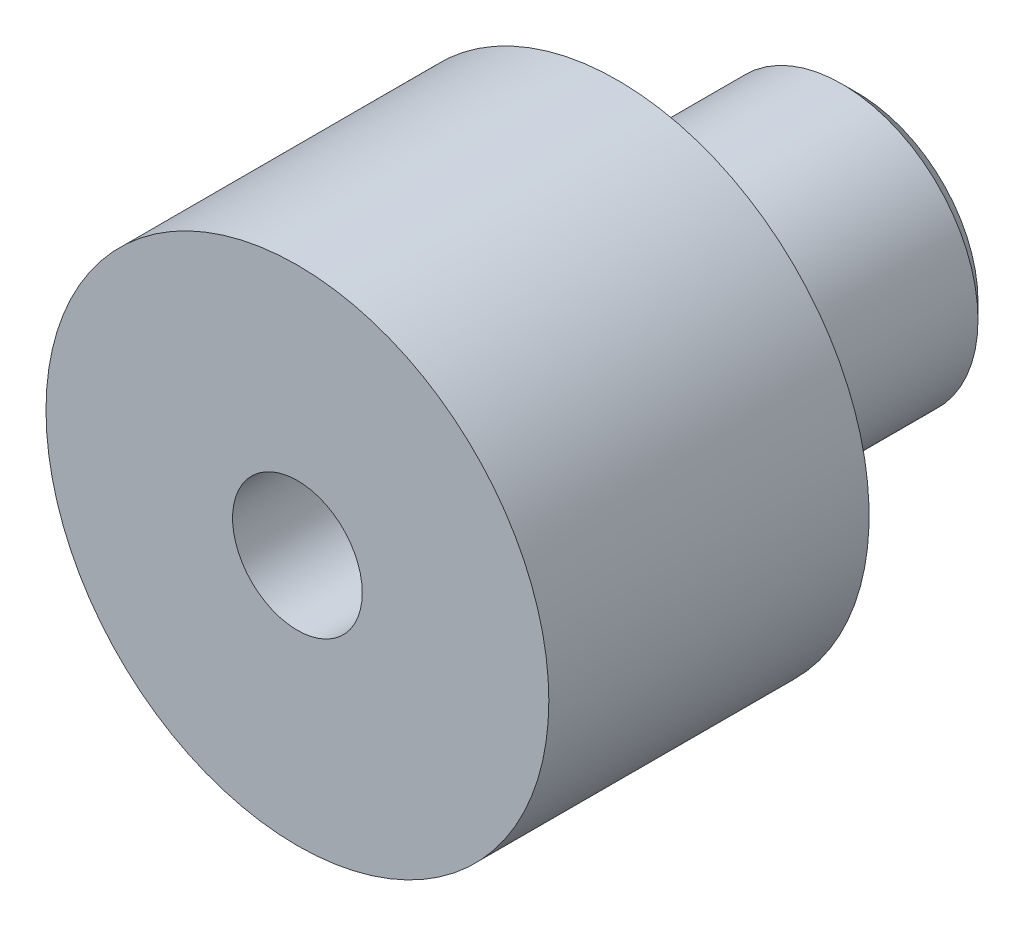
SolidWorks part; units mm, degrees
ref_plane "Front Plane" through (0, 0, 0) normal (0, 0, 1) x (1, 0, 0)
ref_plane "Top Plane" through (0, 0, 0) normal (0, 1, 0) x (1, 0, 0)
ref_plane "Right Plane" through (0, 0, 0) normal (1, 0, 0) x (0, 0, -1)
sketch "Sketch1" plane through (0, 0, 0) normal (0, 0, 1) x (1, 0, 0)
  circle A0 centre (0, 0) radius 8.5
  circle A1 centre (0, 0) radius 4.05
  dimension "D1" = 17
  dimension "D2" = 8.1
extrude "Boss-Extrude1" add sketch "Sketch1" along normal blind 30 contours A0 | A1
sketch "Sketch2" plane through (0, 0, 30) normal (0, 0, 1) x (1, 0, 0)
  circle A0 centre (0, 0) radius 10.7
  circle A2 centre (0, 0) radius 15.7
  circle A3 centre (0, 0) radius 8.5 construction
  circle A4 centre (0, 0) radius 4.05 construction
  circle A5 centre (0, 0) radius 8.5
  circle A6 centre (0, 0) radius 4.05
  circle M5 centre (0, 0) radius 8.5
  circle M6 centre (0, 0) radius 4.05
  dimension "D1" = 21.4
  dimension "D2" = 5
extrude "Boss-Extrude2" add sketch "Sketch2" along normal blind 5 contours A0 M5 | A2 A0 | M5 M6
sketch "Sketch3" plane through (0, 0, 30) normal (0, 0, -1) x (-1, 0, 0)
  circle A0 centre (0, 0) radius 10.7 construction
  circle A1 centre (0, 0) radius 10.7
  circle A2 centre (0, 0) radius 15.7 construction
  circle A3 centre (0, 0) radius 15.7
extrude "Boss-Extrude3" add sketch "Sketch3" along normal blind 15
fillet "Fillet1" radius 1 2 edges at (8.5, 0, 30) (-10.7, 0, 30)
chamfer "Chamfer1" distance 1 angle 45 1 edges at (-10.7, 0, 15)
chamfer "Chamfer2" distance 1 angle 45 2 edges at (8.5, 0, 0) (4.05, 0, 0)
